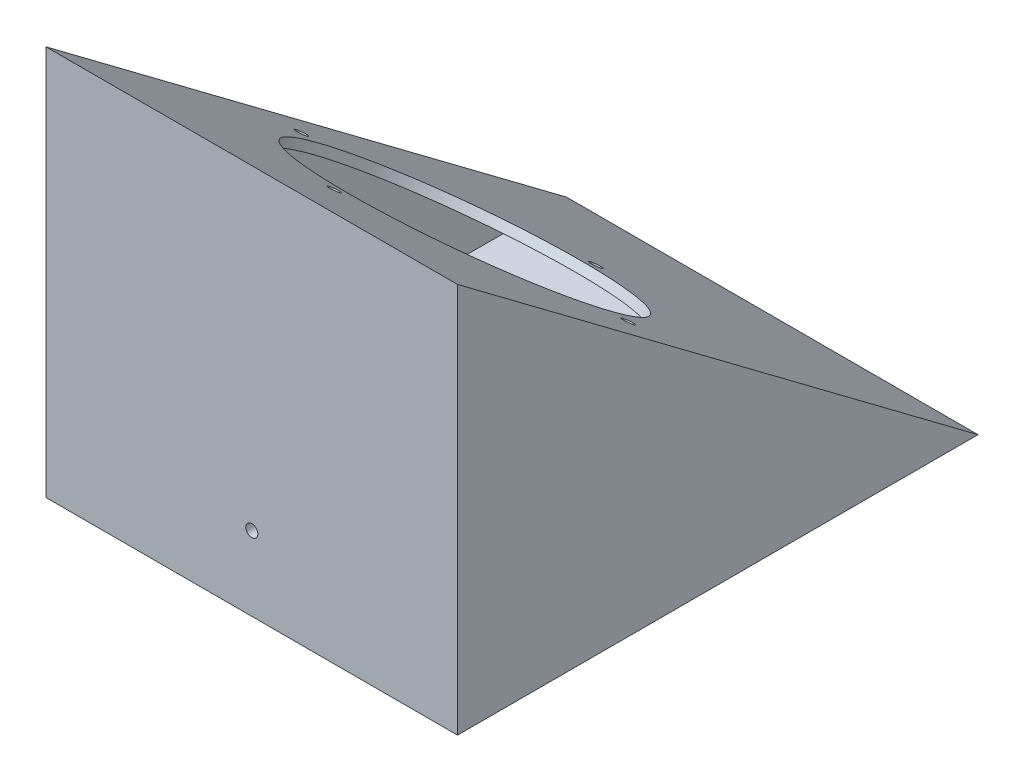
SolidWorks part; units mm, degrees
ref_plane "Front" through (0, 0, 0) normal (0, 0, 1) x (1, 0, 0)
ref_plane "Top" through (0, 0, 0) normal (0, 1, 0) x (1, 0, 0)
ref_plane "Right" through (0, 0, 0) normal (1, 0, 0) x (0, 0, -1)
sketch "Sketch1" plane through (0, 0, 0) normal (1, 0, 0) x (0, 0, -1)
  line L0 (0, 0) -> (160, 0)
  line L1 (0, 0) -> (0, 120)
  line L2 (0, 120) -> (160, 0)
  line L3 (-3, 126) -> (169, -3)
  line L4 (-3, -3) -> (169, -3)
  line L5 (-3, -3) -> (-3, 126)
  dimension "D1" = 120
  dimension "D2" = 160
  dimension "D3" = 3
extrude "Boss-Extrude1" add sketch "Sketch1" along normal blind 130
sketch "Sketch2" plane through (0, 79.2, -59.4) normal (0, 0.8, -0.6) x (1, 0, 0)
  line L0 (130, -78) -> (0, -78) construction
  line L1 (0, 137) -> (0, -78) construction
  circle A0 centre (65, 10) radius 48
  point P2 (0, 0)
  dimension "D1" = 96
  dimension "D2" = 88
  dimension "D3" = 65
extrude "Cut-Extrude1" cut sketch "Sketch2" against normal blind 3
sketch "Sketch3" plane through (0, 79.2, -59.4) normal (0, 0.8, -0.6) x (1, 0, 0)
  circle A0 centre (65, 10) radius 54
  circle A1 centre (11, 10) radius 1.9
  circle A2 centre (65, -44) radius 1.9
  circle A3 centre (119, 10) radius 1.9
  circle A4 centre (65, 64) radius 1.9
  dimension "D1" = 108
  dimension "D2" = 3.8
  dimension "D3" = 3.8
  dimension "D4" = 3.8
  dimension "D5" = 3.8
extrude "Cut-Extrude2" cut sketch "Sketch3" against normal blind 3 contours A0 A2 | A0 A2 | A0 A1 | A0 A1 | A0 A4 | A0 A4 | A0 A3 | A0 A3
sketch "Sketch4" plane through (130, 0, 0) normal (1, 0, 0) x (0, 0, -1)
  line L0 (-3, -3) -> (-3, 126)
  line L1 (-3, 126) -> (169, -3)
  line L2 (169, -3) -> (-3, -3)
extrude "Boss-Extrude2" add sketch "Sketch4" along normal blind 3
sketch "Sketch5" plane through (0, 0, 0) normal (-1, 0, 0) x (0, 0, 1)
  line L0 (3, 126) -> (3, -3)
  line L1 (3, -3) -> (-169, -3)
  line L2 (-169, -3) -> (3, 126)
extrude "Boss-Extrude3" add sketch "Sketch5" along normal blind 3
sketch "Sketch6" plane through (0, 0, 3) normal (0, 0, 1) x (1, 0, 0)
  circle A0 centre (65, 21.5606) radius 2
  dimension "D1" = 4
extrude "Cut-Extrude3" cut sketch "Sketch6" against normal blind 3
